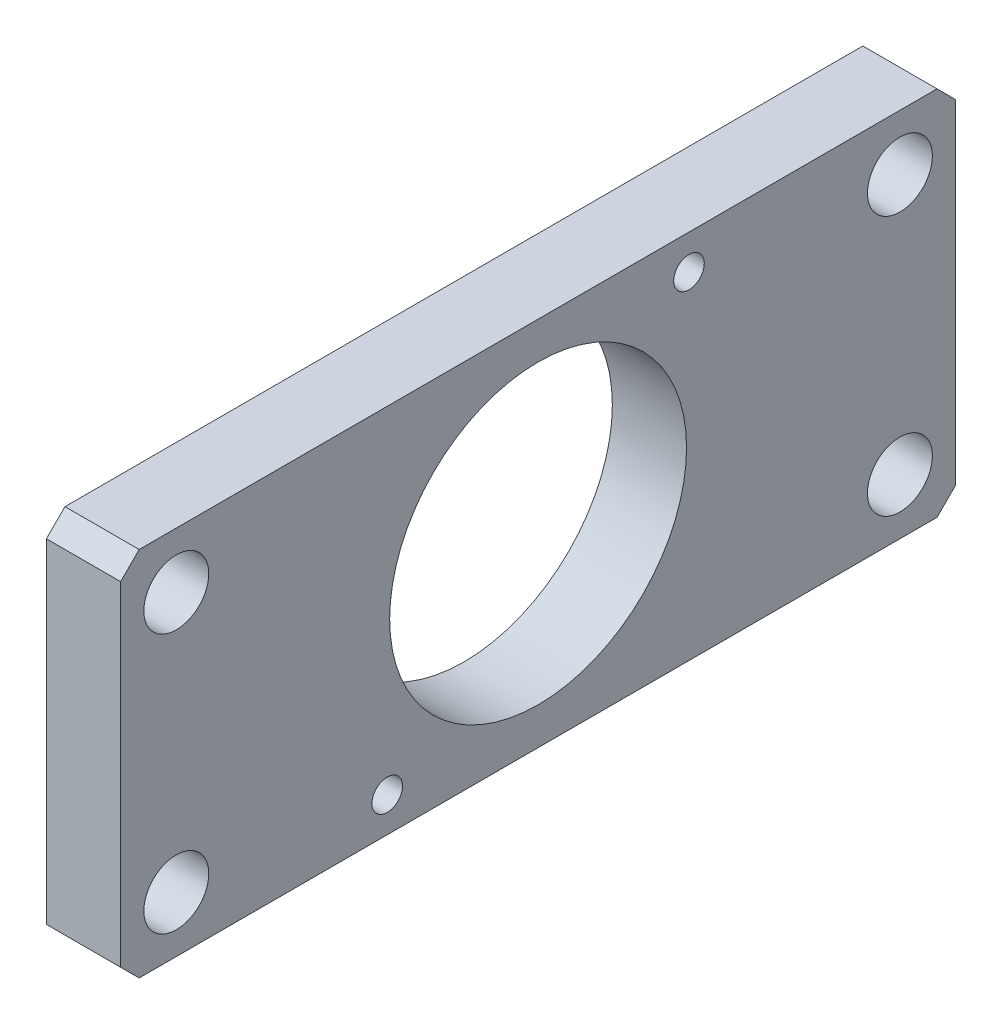
SolidWorks part; units mm, degrees
ref_plane "Front" through (0, 0, 0) normal (0, 0, 1) x (1, 0, 0)
ref_plane "Top" through (0, 0, 0) normal (0, 1, 0) x (1, 0, 0)
ref_plane "Right" through (0, 0, 0) normal (1, 0, 0) x (0, 0, -1)
sketch "Sketch1" plane through (0, 0, 0) normal (1, 0, 0) x (0, 0, -1)
  line L0 (0, 50.8425) -> (0, -7.3924) construction
  line L1 (45, 0) -> (-45, 0)
  line L2 (45, 0) -> (45, 40)
  line L3 (45, 40) -> (-45, 40)
  line L4 (-45, 0) -> (-45, 40)
  dimension "D1" = 90
  dimension "D2" = 40
extrude "Boss-Extrude1" add sketch "Sketch1" along normal blind 8
sketch "Sketch2" plane through (8, 0, 0) normal (1, 0, 0) x (0, 0, -1)
  line L0 (-45, 0) -> (45, 0) construction
  circle A0 centre (0, 20) radius 16
  dimension "D1" = 32
  dimension "D2" = 20
extrude "Cut-Extrude1" cut sketch "Sketch2" against normal through all
hole_wizard "Ø7.0 (7) Diameter Hole1" positions "Sketch4" profile "Sketch3" hole size "Ø7.0" standard "JIS"
sketch "Sketch4" plane through (8, 0, 0) normal (1, 0, 0) x (0, 0, -1)
  line L0 (0, 45.8404) -> (0, -7.0709) construction
  line L2 (-45, 0) -> (45, 0) construction
  point P0 (-39, 6)
  point P1 (39, 6)
  point P3 (39, 34)
  point P5 (-39, 34)
  dimension "D1" = 78
  dimension "D2" = 28
  dimension "D3" = 6
sketch "Sketch3" plane through (8, 6, 39) normal (0, 1, 0) x (0, 0, -1)
  line L0 (0, 0) -> (0, 62.103)
  line L1 (0, 62.103) -> (3.5, 60)
  line L2 (3.5, 60) -> (3.5, 0)
  line L5 (3.5, 0) -> (0, 0)
  line L10 (0, 62.103) -> (-3.5, 60) construction
  line L11 (0, -6.35) -> (0, 107.95) construction
  dimension "Hole Dia." = 7
  dimension "Hole Depth" = 60
  dimension "Drill Angle" = 118
hole_wizard "M4x0.7 Tapped Hole1" positions "Sketch6" profile "Sketch5" tap size "M4x0.7" standard "JIS" end condition through all
sketch "Sketch6" plane through (8, 0, 0) normal (1, 0, 0) x (0, 0, -1)
  line L0 (0, 48.1698) -> (0, -5.9468) construction
  line L2 (-20.9327, -0.9327) -> (22.7503, 42.7503) construction
  circle A0 centre (0, 20) radius 23 construction
  circle A1 centre (0, 20) radius 16 construction
  point P1 (16.2635, 36.2635)
  point P5 (-16.2635, 3.7365)
  dimension "D1" = 46
  dimension "D2" = 45
sketch "Sketch5" plane through (8, 36.2635, -16.2635) normal (0, 1, 0) x (0, 0, -1)
  line L0 (0, 0) -> (0, 8)
  line L1 (0, 8) -> (1.65, 8)
  line L2 (1.65, 8) -> (1.65, 0)
  line L5 (1.65, 0) -> (0, 0)
  line L11 (0, -6.35) -> (0, 107.95) construction
  dimension "Thru Tap Drill Dia." = 3.3
  dimension "Thru Tap Drill Depth" = 8
cosmetic thread "Hole Thread1"
cosmetic thread "Hole Thread2"
chamfer "Chamfer1" distance 2 angle 45 4 edges at (4, 0, 45) (4, 0, -45) (4, 40, -45) (4, 40, 45)
